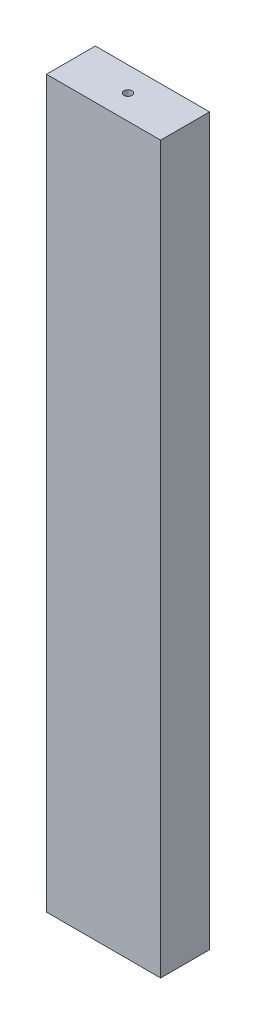
SolidWorks part; units mm, degrees
material "Balsa"
ref_plane "Front Plane" through (0, 0, 0) normal (0, 0, 1) x (1, 0, 0)
ref_plane "Top Plane" through (0, 0, 0) normal (0, 1, 0) x (1, 0, 0)
ref_plane "Right Plane" through (0, 0, 0) normal (1, 0, 0) x (0, 0, -1)
sketch "Sketch1" plane through (0, 0, 0) normal (0, 1, 0) x (1, 0, 0)
  line L1 (0, 0) -> (88.9, 0)
  line L2 (0, 0) -> (0, 38.1)
  line L3 (0, 38.1) -> (88.9, 38.1)
  line L4 (88.9, 0) -> (88.9, 38.1)
  dimension "D1" = 88.9
  dimension "D2" = 38.1
extrude "Boss-Extrude1" add sketch "Sketch1" along normal blind 565.15
sketch "Sketch2" plane through (0, 0, 0) normal (0, -1, 0) x (-1, 0, 0)
  line L0 (-88.9, 0) -> (-88.9, 38.1) construction
  line L1 (0, 0) -> (-88.9, 0) construction
  circle A0 centre (-44.45, 19.05) radius 3.175
  dimension "D1" = 6.35
  dimension "D2" = 44.45
  dimension "D3" = 19.05
extrude "Cut-Extrude1" cut sketch "Sketch2" against normal blind 565.15
